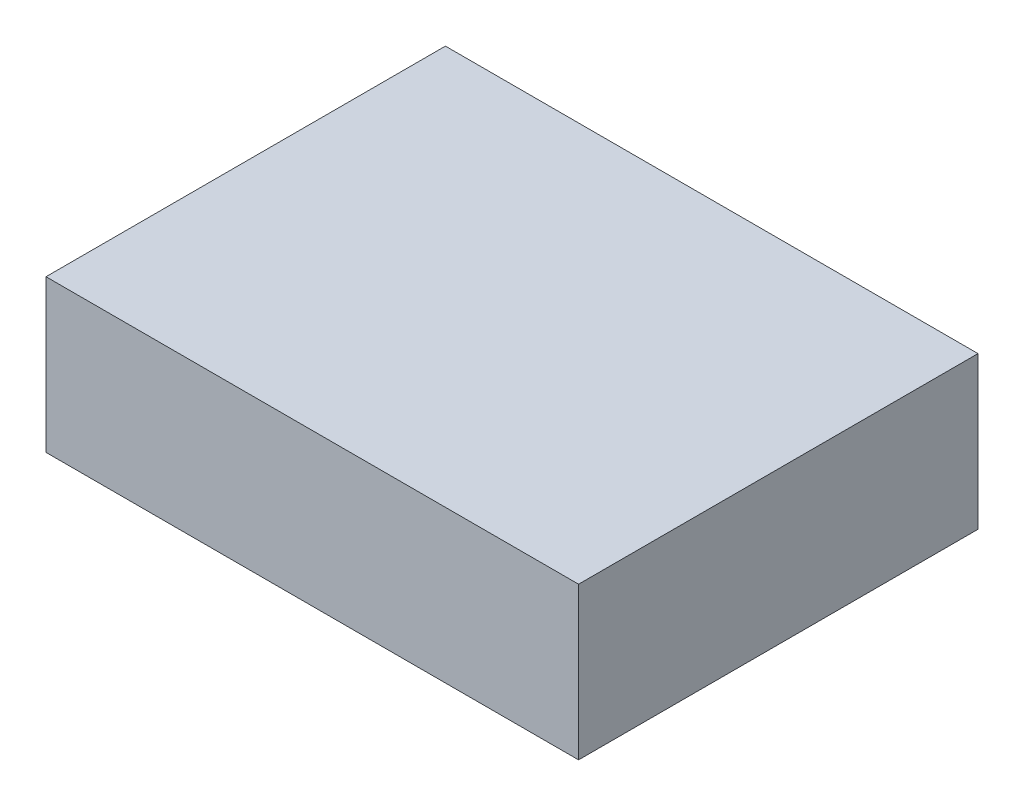
SolidWorks part; units mm, degrees
ref_plane "Front Plane" through (0, 0, 0) normal (0, 0, 1) x (1, 0, 0)
ref_plane "Top Plane" through (0, 0, 0) normal (0, 1, 0) x (1, 0, 0)
ref_plane "Right Plane" through (0, 0, 0) normal (1, 0, 0) x (0, 0, -1)
sketch "Sketch1" plane through (0, 0, 0) normal (0, 1, 0) x (1, 0, 0)
  line L1 (0, 0) -> (88.9, 0)
  line L2 (0, 0) -> (0, 66.675)
  line L3 (0, 66.675) -> (88.9, 66.675)
  line L4 (88.9, 0) -> (88.9, 66.675)
  dimension "D1" = 66.675
  dimension "D2" = 88.9
extrude "Boss-Extrude1" add sketch "Sketch1" along normal blind 25.4
